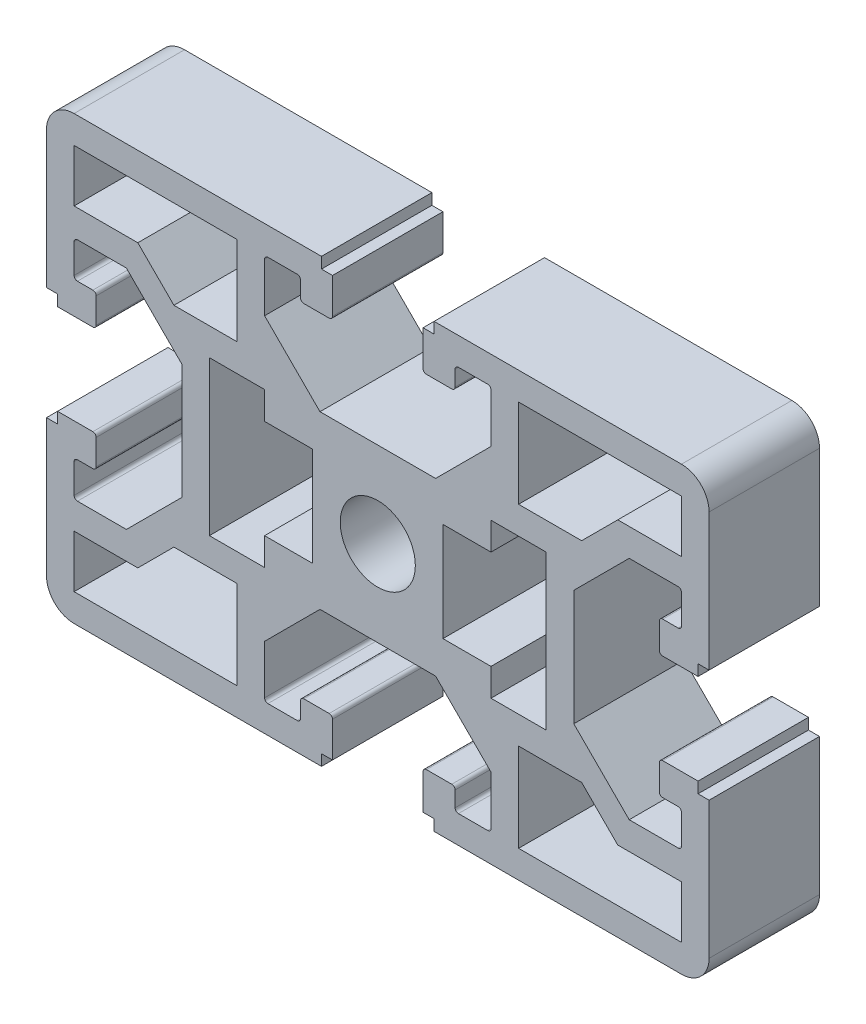
SolidWorks part; units mm, degrees
ref_plane "前视基准面" through (0, 0, 0) normal (0, 0, 1) x (1, 0, 0)
ref_plane "上视基准面" through (0, 0, 0) normal (0, 1, 0) x (1, 0, 0)
ref_plane "右视基准面" through (0, 0, 0) normal (1, 0, 0) x (0, 0, -1)
sketch "草图1" plane through (0, 0, 0) normal (0, 0, 1) x (1, 0, 0)
  line L0 (-5.1905, 20) -> (-27.5905, 20)
  line L1 (-30.0905, 17.5) -> (-30.0905, 5.1)
  line L2 (-7.0905, 15.8) -> (-7.0905, 17.2)
  line L3 (-7.3905, 17.5) -> (-10.0405, 17.5)
  line L4 (-10.3405, 17.2) -> (-10.3405, 12.7655)
  line L5 (-12.8405, 17.5) -> (-27.5905, 17.5)
  line L6 (-27.5905, 17.5) -> (-27.5905, 12.75)
  line L7 (-22.8561, 10.25) -> (-27.2905, 10.25)
  line L8 (-27.5905, 9.95) -> (-27.5905, 7.3)
  line L9 (-27.2905, 7) -> (-25.8905, 7)
  line L10 (-25.5905, 6.7) -> (-25.5905, 4.4)
  line L11 (-25.8905, 4.1) -> (-29.0905, 4.1)
  line L12 (-4.4905, 15.5) -> (-6.7905, 15.5)
  line L13 (-0.0905, 7.75) -> (-5.325, 7.75)
  line L14 (-17.8405, 5.2345) -> (-17.8405, 0)
  line L15 (-15.3405, 6.98) -> (-15.3405, 0)
  line L16 (-5.9905, 4.48) -> (-5.9905, 0)
  line L17 (-29.0905, 5.1) -> (-29.0905, 4.1)
  line L18 (-4.1905, 19) -> (-5.1905, 19)
  line L19 (-27.5905, 12.75) -> (-21.8205, 12.75)
  line L20 (-30.0905, 5.1) -> (-29.0905, 5.1)
  line L21 (-12.8405, 17.5) -> (-12.8405, 12.75)
  line L22 (-12.8405, 10.25) -> (-12.8405, 9.48)
  line L24 (-10.3405, 6.98) -> (-10.3405, 4.48)
  line L25 (-5.1905, 20) -> (-5.1905, 19)
  line L26 (-18.5505, 9.48) -> (-21.8205, 12.75)
  line L27 (-17.8405, 5.2345) -> (-22.8561, 10.25)
  line L28 (-18.5505, 9.48) -> (-12.8405, 9.48)
  line L30 (-12.8405, 10.25) -> (-12.8405, 12.75)
  line L31 (-15.3405, 6.98) -> (-10.3405, 6.98)
  line L32 (-10.3405, 4.48) -> (-5.9905, 4.48)
  line L35 (-4.1905, 15.8) -> (-4.1905, 19)
  line L36 (-5.325, 7.75) -> (-10.3405, 12.7655)
  line L37 (5.0095, 20) -> (27.4095, 20)
  line L38 (29.9095, 17.5) -> (29.9095, 5.1)
  line L39 (7.2095, 17.5) -> (9.8595, 17.5)
  line L40 (12.6595, 17.5) -> (27.4095, 17.5)
  line L41 (27.4095, 17.5) -> (27.4095, 12.75)
  line L42 (4.3095, 15.5) -> (6.6095, 15.5)
  line L43 (22.675, 10.25) -> (27.1095, 10.25)
  line L44 (27.4095, 9.95) -> (27.4095, 7.3)
  line L45 (27.1095, 7) -> (25.7095, 7)
  line L46 (25.4095, 6.7) -> (25.4095, 4.4)
  line L47 (25.7095, 4.1) -> (28.9095, 4.1)
  line L48 (-0.0905, 7.75) -> (5.1439, 7.75)
  line L49 (17.6595, 5.2345) -> (17.6595, 0)
  line L50 (15.1595, 6.98) -> (15.1595, 0)
  line L51 (5.8095, 4.48) -> (5.8095, 0)
  line L52 (28.9095, 5.1) -> (28.9095, 4.1)
  line L53 (4.0095, 19) -> (5.0095, 19)
  line L54 (27.4095, 12.75) -> (21.6395, 12.75)
  line L55 (29.9095, 5.1) -> (28.9095, 5.1)
  line L56 (6.9095, 17.2) -> (6.9095, 15.8)
  line L57 (12.6595, 17.5) -> (12.6595, 12.75)
  line L58 (12.6595, 10.25) -> (12.6595, 9.48)
  line L60 (10.1595, 17.2) -> (10.1595, 12.7655)
  line L61 (10.1595, 6.98) -> (10.1595, 4.48)
  line L62 (5.0095, 20) -> (5.0095, 19)
  line L63 (18.3695, 9.48) -> (21.6395, 12.75)
  line L64 (17.6595, 5.2345) -> (22.675, 10.25)
  line L65 (18.3695, 9.48) -> (12.6595, 9.48)
  line L67 (12.6595, 10.25) -> (12.6595, 12.75)
  line L68 (15.1595, 6.98) -> (10.1595, 6.98)
  line L69 (10.1595, 4.48) -> (5.8095, 4.48)
  line L74 (4.0095, 15.8) -> (4.0095, 19)
  line L75 (5.1439, 7.75) -> (10.1595, 12.7655)
  line L76 (-5.1905, -20) -> (-27.5905, -20)
  line L77 (-30.0905, -17.5) -> (-30.0905, -5.1)
  line L78 (-7.3905, -17.5) -> (-10.0405, -17.5)
  line L79 (-12.8405, -17.5) -> (-27.5905, -17.5)
  line L80 (-27.5905, -17.5) -> (-27.5905, -12.75)
  line L81 (-4.4905, -15.5) -> (-6.7905, -15.5)
  line L82 (-22.8561, -10.25) -> (-27.2905, -10.25)
  line L83 (-27.5905, -9.95) -> (-27.5905, -7.3)
  line L84 (-27.2905, -7) -> (-25.8905, -7)
  line L85 (-25.5905, -6.7) -> (-25.5905, -4.4)
  line L86 (-25.8905, -4.1) -> (-29.0905, -4.1)
  line L87 (-0.0905, -7.75) -> (-5.325, -7.75)
  line L88 (-17.8405, -5.2345) -> (-17.8405, 0)
  line L89 (-15.3405, -6.98) -> (-15.3405, 0)
  line L90 (-5.9905, -4.48) -> (-5.9905, 0)
  line L91 (-29.0905, -5.1) -> (-29.0905, -4.1)
  line L92 (-4.1905, -19) -> (-5.1905, -19)
  line L93 (-27.5905, -12.75) -> (-21.8205, -12.75)
  line L94 (-30.0905, -5.1) -> (-29.0905, -5.1)
  line L95 (-7.0905, -17.2) -> (-7.0905, -15.8)
  line L96 (-12.8405, -17.5) -> (-12.8405, -12.75)
  line L97 (-12.8405, -10.25) -> (-12.8405, -9.48)
  line L99 (-10.3405, -17.2) -> (-10.3405, -12.7655)
  line L100 (-10.3405, -6.98) -> (-10.3405, -4.48)
  line L101 (-5.1905, -20) -> (-5.1905, -19)
  line L102 (-18.5505, -9.48) -> (-21.8205, -12.75)
  line L103 (-17.8405, -5.2345) -> (-22.8561, -10.25)
  line L104 (-18.5505, -9.48) -> (-12.8405, -9.48)
  line L106 (-12.8405, -10.25) -> (-12.8405, -12.75)
  line L107 (-15.3405, -6.98) -> (-10.3405, -6.98)
  line L108 (-10.3405, -4.48) -> (-5.9905, -4.48)
  line L113 (-4.1905, -15.8) -> (-4.1905, -19)
  line L114 (-5.325, -7.75) -> (-10.3405, -12.7655)
  line L115 (5.0095, -20) -> (27.4095, -20)
  line L116 (29.9095, -17.5) -> (29.9095, -5.1)
  line L117 (7.2095, -17.5) -> (9.8595, -17.5)
  line L118 (12.6595, -17.5) -> (27.4095, -17.5)
  line L119 (27.4095, -17.5) -> (27.4095, -12.75)
  line L120 (4.3095, -15.5) -> (6.6095, -15.5)
  line L121 (22.675, -10.25) -> (27.1095, -10.25)
  line L122 (27.4095, -9.95) -> (27.4095, -7.3)
  line L123 (27.1095, -7) -> (25.7095, -7)
  line L124 (25.4095, -6.7) -> (25.4095, -4.4)
  line L125 (25.7095, -4.1) -> (28.9095, -4.1)
  line L126 (-0.0905, -7.75) -> (5.1439, -7.75)
  line L127 (17.6595, -5.2345) -> (17.6595, 0)
  line L128 (15.1595, -6.98) -> (15.1595, 0)
  line L129 (5.8095, -4.48) -> (5.8095, 0)
  line L130 (28.9095, -5.1) -> (28.9095, -4.1)
  line L131 (4.0095, -19) -> (5.0095, -19)
  line L132 (27.4095, -12.75) -> (21.6395, -12.75)
  line L133 (29.9095, -5.1) -> (28.9095, -5.1)
  line L134 (6.9095, -17.2) -> (6.9095, -15.8)
  line L135 (12.6595, -17.5) -> (12.6595, -12.75)
  line L136 (12.6595, -10.25) -> (12.6595, -9.48)
  line L138 (10.1595, -17.2) -> (10.1595, -12.7655)
  line L139 (10.1595, -6.98) -> (10.1595, -4.48)
  line L140 (5.0095, -20) -> (5.0095, -19)
  line L141 (18.3695, -9.48) -> (21.6395, -12.75)
  line L142 (17.6595, -5.2345) -> (22.675, -10.25)
  line L143 (18.3695, -9.48) -> (12.6595, -9.48)
  line L145 (12.6595, -10.25) -> (12.6595, -12.75)
  line L146 (15.1595, -6.98) -> (10.1595, -6.98)
  line L147 (10.1595, -4.48) -> (5.8095, -4.48)
  line L152 (4.0095, -15.8) -> (4.0095, -19)
  line L153 (5.1439, -7.75) -> (10.1595, -12.7655)
  arc A0 (-27.5905, 20) -> (-30.0905, 17.5) centre (-27.5905, 17.5) ccw
  arc A1 (-7.0905, 17.2) -> (-7.3905, 17.5) centre (-7.3905, 17.2) ccw
  arc A2 (-10.0405, 17.5) -> (-10.3405, 17.2) centre (-10.0405, 17.2) ccw
  arc A3 (-27.2905, 10.25) -> (-27.5905, 9.95) centre (-27.2905, 9.95) ccw
  arc A4 (-27.5905, 7.3) -> (-27.2905, 7) centre (-27.2905, 7.3) ccw
  arc A5 (-25.5905, 6.7) -> (-25.8905, 7) centre (-25.8905, 6.7) ccw
  arc A6 (-25.8905, 4.1) -> (-25.5905, 4.4) centre (-25.8905, 4.4) ccw
  circle A7 centre (-0.0905, 0) radius 3.4
  arc A8 (-7.0905, 15.8) -> (-6.7905, 15.5) centre (-6.7905, 15.8) ccw
  arc A9 (-4.4905, 15.5) -> (-4.1905, 15.8) centre (-4.4905, 15.8) ccw
  arc A10 (29.9095, 17.5) -> (27.4095, 20) centre (27.4095, 17.5) ccw
  arc A11 (27.4095, 9.95) -> (27.1095, 10.25) centre (27.1095, 9.95) ccw
  arc A12 (27.1095, 7) -> (27.4095, 7.3) centre (27.1095, 7.3) ccw
  arc A13 (25.7095, 7) -> (25.4095, 6.7) centre (25.7095, 6.7) ccw
  arc A14 (25.4095, 4.4) -> (25.7095, 4.1) centre (25.7095, 4.4) ccw
  arc A15 (10.1595, 17.2) -> (9.8595, 17.5) centre (9.8595, 17.2) ccw
  arc A16 (7.2095, 17.5) -> (6.9095, 17.2) centre (7.2095, 17.2) ccw
  arc A17 (6.6095, 15.5) -> (6.9095, 15.8) centre (6.6095, 15.8) ccw
  arc A18 (4.0095, 15.8) -> (4.3095, 15.5) centre (4.3095, 15.8) ccw
  arc A19 (-30.0905, -17.5) -> (-27.5905, -20) centre (-27.5905, -17.5) ccw
  arc A20 (-27.5905, -9.95) -> (-27.2905, -10.25) centre (-27.2905, -9.95) ccw
  arc A21 (-27.2905, -7) -> (-27.5905, -7.3) centre (-27.2905, -7.3) ccw
  arc A22 (-25.8905, -7) -> (-25.5905, -6.7) centre (-25.8905, -6.7) ccw
  arc A23 (-25.5905, -4.4) -> (-25.8905, -4.1) centre (-25.8905, -4.4) ccw
  arc A24 (-10.3405, -17.2) -> (-10.0405, -17.5) centre (-10.0405, -17.2) ccw
  arc A25 (-7.3905, -17.5) -> (-7.0905, -17.2) centre (-7.3905, -17.2) ccw
  arc A26 (-6.7905, -15.5) -> (-7.0905, -15.8) centre (-6.7905, -15.8) ccw
  arc A27 (-4.1905, -15.8) -> (-4.4905, -15.5) centre (-4.4905, -15.8) ccw
  arc A28 (27.4095, -20) -> (29.9095, -17.5) centre (27.4095, -17.5) ccw
  arc A29 (27.1095, -10.25) -> (27.4095, -9.95) centre (27.1095, -9.95) ccw
  arc A30 (27.4095, -7.3) -> (27.1095, -7) centre (27.1095, -7.3) ccw
  arc A31 (25.4095, -6.7) -> (25.7095, -7) centre (25.7095, -6.7) ccw
  arc A32 (25.7095, -4.1) -> (25.4095, -4.4) centre (25.7095, -4.4) ccw
  arc A33 (9.8595, -17.5) -> (10.1595, -17.2) centre (9.8595, -17.2) ccw
  arc A34 (6.9095, -17.2) -> (7.2095, -17.5) centre (7.2095, -17.2) ccw
  arc A35 (6.9095, -15.8) -> (6.6095, -15.5) centre (6.6095, -15.8) ccw
  arc A36 (4.3095, -15.5) -> (4.0095, -15.8) centre (4.3095, -15.8) ccw
extrude "凸台-拉伸1" add sketch "草图1" along normal blind 10
